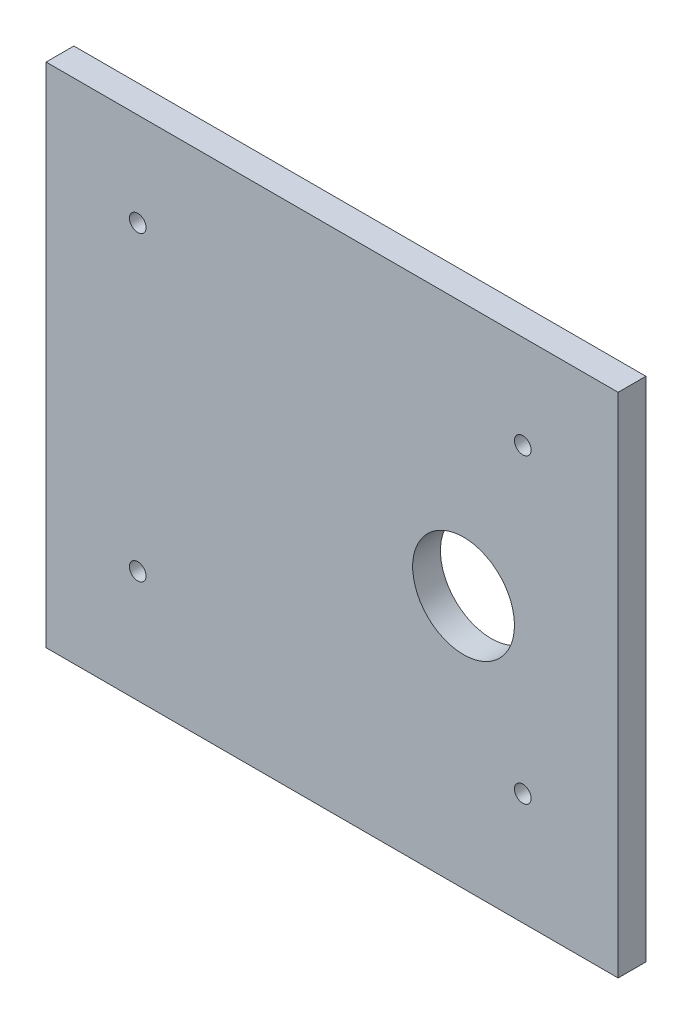
SolidWorks part; units mm, degrees
ref_plane "Alzado" through (0, 0, 0) normal (1, 0, 0) x (0, 1, 0)
ref_plane "Planta" through (0, 0, 0) normal (0, 0, 1) x (0, 1, 0)
ref_plane "Vista lateral" through (0, 0, 0) normal (0, 1, 0) x (-1, 0, 0)
sketch "Croquis2" plane through (0, 0, 0) normal (0, 0, 1) x (0, 1, 0)
  line L0 (-58.904, 83.5) -> (337.2899, 83.5) construction
  line L1 (0, 0) -> (274, 0)
  line L2 (0, 0) -> (0, 309)
  line L3 (0, 309) -> (274, 309)
  line L4 (274, 0) -> (274, 309)
  line L5 (137, -336.1498) -> (137, 336.1498) construction
  line L6 (60.5, 336.1498) -> (60.5, -82.3707) construction
  line L7 (223.5, 336.1498) -> (223.5, -82.3707) construction
  line L8 (-31.6062, 51.5) -> (323.2758, 51.5) construction
  line L9 (-42.0057, 259.5) -> (323.2758, 259.5) construction
  circle A0 centre (137, 83.5) radius 27.5
  circle A1 centre (60.5, 51.5) radius 4.5
  circle A2 centre (223.5, 51.5) radius 4.5
  circle A3 centre (60.5, 259.5) radius 4.5
  circle A4 centre (223.5, 259.5) radius 4.5
  point P10 (137, 0)
  point P28 (60.5, 259.5)
  dimension "D4" = 55
  dimension "D9" = 9
  dimension "D1" = 309
  dimension "D2" = 274
  dimension "D3" = 83.5
  dimension "D5" = 49.5
  dimension "D6" = 60.5
  dimension "D7" = 50.5
  dimension "D8" = 51.5
extrude "Saliente-Extruir1" add sketch "Croquis2" along normal blind 15
